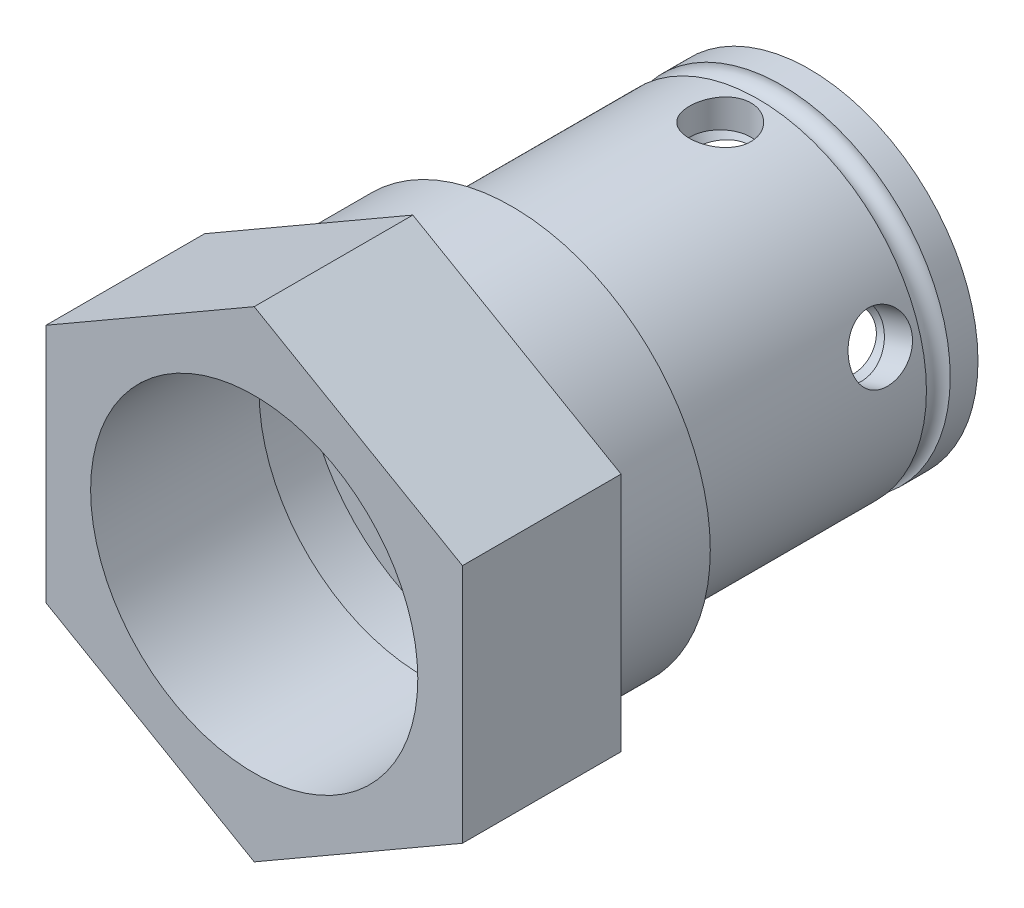
SolidWorks part; units mm, degrees
ref_plane "前视基准面" through (0, 0, 0) normal (0, 0, 1) x (1, 0, 0)
ref_plane "上视基准面" through (0, 0, 0) normal (0, 1, 0) x (1, 0, 0)
ref_plane "右视基准面" through (0, 0, 0) normal (1, 0, 0) x (0, 0, -1)
sketch "草图2" plane through (0, 0, 0) normal (0, 0, 1) x (1, 0, 0)
  circle A0 centre (0, 0) radius 8.5
  dimension "D1" = 17
extrude "凸台-拉伸1" add sketch "草图2" along normal blind 15
sketch "草图3" plane through (0, 0, 15) normal (0, 0, 1) x (1, 0, 0)
  circle A0 centre (0, 0) radius 10
  dimension "D1" = 20
extrude "凸台-拉伸2" add sketch "草图3" along normal blind 5
sketch "草图4" plane through (0, 0, 20) normal (0, 0, 1) x (1, 0, 0)
  line L1 (0, 12.1244) -> (-10.5, 6.0622)
  line L2 (-10.5, 6.0622) -> (-10.5, -6.0622)
  line L3 (-10.5, -6.0622) -> (0, -12.1244)
  line L4 (0, -12.1244) -> (10.5, -6.0622)
  line L5 (10.5, -6.0622) -> (10.5, 6.0622)
  line L6 (10.5, 6.0622) -> (0, 12.1244)
  circle A0 centre (0, 0) radius 10.5 construction
  dimension "D1" = 21
extrude "凸台-拉伸3" add sketch "草图4" along normal blind 8
sketch "草图6" plane through (0, 0, 0) normal (0, 0, -1) x (-1, 0, 0)
  circle A0 centre (0, 0) radius 6.75
  dimension "D1" = 13.5
extrude "切除-拉伸1" cut sketch "草图6" against normal blind 15
sketch "草图7" plane through (0, 0, 15) normal (0, 0, -1) x (-1, 0, 0)
  circle A0 centre (0, 0) radius 5.9
  dimension "D1" = 11.8
extrude "切除-拉伸2" cut sketch "草图7" against normal through all
sketch "草图8" plane through (0, 0, 0) normal (1, 0, 0) x (0, 0, -1)
  line L0 (-5.2795, 0) -> (-39.7814, 0) construction
  line L1 (11.55, 0) -> (-11.55, 0) construction
  line L2 (-16.7, 0) -> (-16.7, -6.9)
  line L3 (-16.7, -6.9) -> (-16.5, -6.9)
  line L4 (-16.5, -6.9) -> (-16.5, -9)
  line L5 (-16.5, -9) -> (-19.5, -9)
  line L6 (-19.5, -9) -> (-19.5, 0)
  line L7 (-28, -6.0622) -> (-28, -12.1244) construction
  line L8 (-16.7, 0) -> (-19.5, 0)
  dimension "D1" = 3
  dimension "D2" = 0.2
  dimension "D3" = 18
  dimension "D4" = 6.9
  dimension "D5" = 11.5
revolve "切除-旋转1" cut sketch "草图8" angle 360 about L0
sketch "草图9" plane through (0, 0, 0) normal (0, 0, 1) x (1, 0, 0)
  point P0 (0, 0)
hole_wizard "M18x1.5 螺纹孔1" positions "草图10" profile "草图11" tap size "M18x1.5" standard "GB"
sketch "草图10" plane through (0, 0, 28) normal (0, 0, 1) x (1, 0, 0)
  point P0 (0, 0)
sketch "草图11" plane through (0, 0, 28) normal (1, 0, 0) x (0, -1, 0)
  line L0 (0, 0) -> (0, 11.9571)
  line L1 (0, 11.9571) -> (8.25, 7)
  line L2 (8.25, 7) -> (8.25, 0)
  line L5 (8.25, 0) -> (0, 0)
  line L10 (0, 11.9571) -> (-8.25, 7) construction
  line L11 (0, -6.35) -> (0, 107.95) construction
  dimension "螺纹孔钻头直径" = 16.5
  dimension "螺纹孔钻头深度" = 7
  dimension "导头角度" = 118
cosmetic thread "孔螺纹线1" parameters "D1"=7, "D2"=18
sketch "草图13" plane through (0, 0, 0) normal (0, 0, 1) x (1, 0, 0)
  circle A0 centre (0, 0) radius 8.25 construction
  circle A1 centre (0, 0) radius 8.25
extrude "切除-拉伸3" cut sketch "草图13" against normal up to next from surface
ref_plane "基准面1" through (0, 0, 2) normal (0, 0, 1) x (1, 0, 0)
sketch "草图14" plane through (0, 0, 2) normal (0, 0, 1) x (1, 0, 0)
  circle A0 centre (0, 0) radius 8.5
  dimension "D1" = 17
sweep "切除-扫描1" cut path "草图14" circular profile diameter 1.2 parameters "D3"=1.2
ref_plane "基准面2" through (0, 8.5, 0) normal (0, 1, 0) x (1, 0, 0)
sketch "草图20" plane through (0, 8.5, 0) normal (0, 1, 0) x (1, 0, 0)
  line L0 (0, -13.3368) -> (0, 13.3368) construction
  line L1 (-11.55, 0) -> (11.55, 0) construction
  point P0 (0, -4.5)
  dimension "D1" = 4.5
hole_wizard "Ø3.1 (3.1) 直径孔1" positions "草图21" profile "草图22" hole size "Ø3.1" standard "GB"
sketch "草图21" plane through (0, 8.5, 0) normal (0, 1, 0) x (1, 0, 0)
  point P0 (0, -4.5)
sketch "草图22" plane through (0, 8.5, 4.5) normal (1, 0, 0) x (0, 0, 1)
  line L0 (0, 0) -> (0, 4.1847)
  line L1 (0, 4.1847) -> (1.55, 1.5)
  line L2 (1.55, 1.5) -> (1.55, 0)
  line L5 (1.55, 0) -> (0, 0)
  line L10 (0, 4.1847) -> (-1.55, 1.5) construction
  line L11 (0, -6.35) -> (0, 107.95) construction
  dimension "孔直径" = 3.1
  dimension "孔深度" = 1.5
  dimension "导头角度" = 60
pattern_circular "阵列(圆周)1" count 5 over 360 about axis through (0, 0, 0) along (0, 0, 1) of "Ø3.1 (3.1) 直径孔1"
